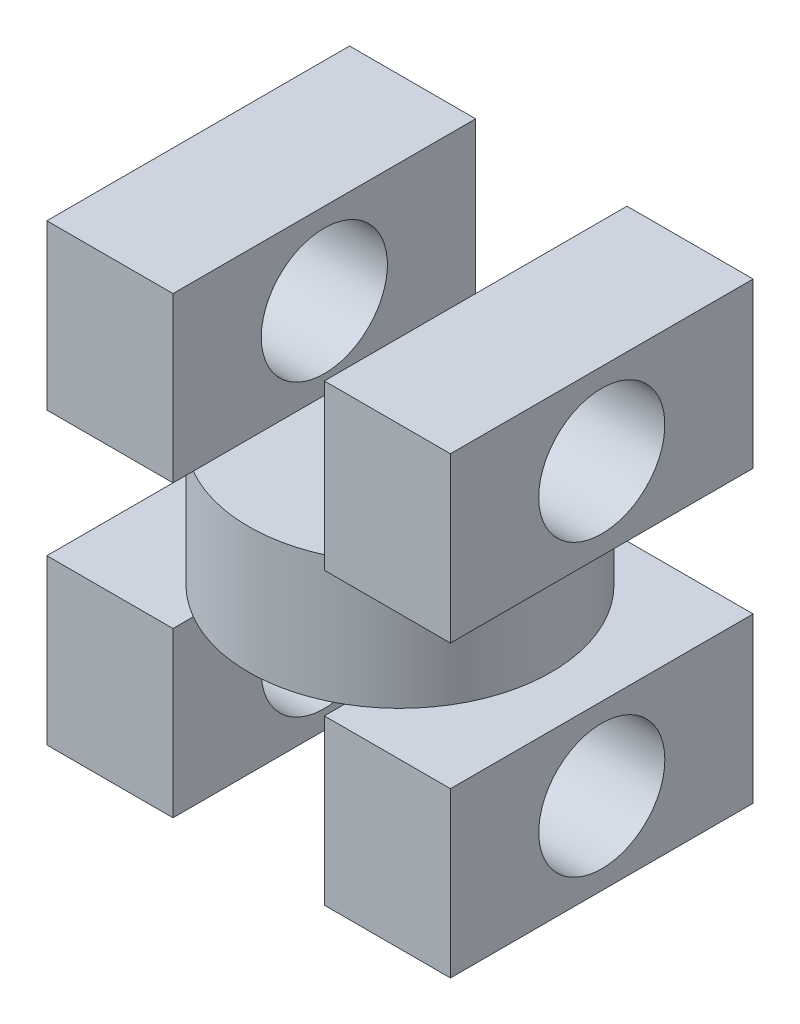
SolidWorks part; units mm, degrees
ref_plane "Front Plane" through (0, 0, 0) normal (0, 0, 1) x (1, 0, 0)
ref_plane "Top Plane" through (0, 0, 0) normal (0, 1, 0) x (1, 0, 0)
ref_plane "Right Plane" through (0, 0, 0) normal (1, 0, 0) x (0, 0, -1)
sketch "Sketch1" plane through (0, 0, 0) normal (0, 0, 1) x (1, 0, 0)
  line L0 (0, 0) -> (0, 13)
  line L1 (0, 13) -> (-32, 13)
  line L2 (-32, 13) -> (-32, 0)
  line L3 (-32, 0) -> (0, 0)
extrude "Boss-Extrude1" add sketch "Sketch1" along normal blind 24
sketch "Sketch2" plane through (0, 0, 0) normal (0, 0, -1) x (-1, 0, 0)
  line L0 (0, 13) -> (10, 13)
  line L1 (0, 13) -> (32, 13) construction
  line L2 (10, 13) -> (10, 0)
  line L3 (32, 0) -> (0, 0) construction
  line L4 (10, 0) -> (22, 0)
  line L5 (22, 0) -> (22, 13)
  line L6 (22, 13) -> (10, 13)
  line M1 (0, 0) -> (32, 0)
  line M3 (32, 13) -> (0, 13)
extrude "Cut-Extrude1" cut sketch "Sketch2" against normal through all contours L5 L2 M1 M3
sketch "Sketch3" plane through (0, 0, 0) normal (1, 0, 0) x (0, 0, -1)
  line L0 (0, 6.5) -> (-12, 6.5)
  line L1 (0, 0) -> (0, 13) construction
  circle A0 centre (-12, 6.5) radius 4.5
extrude "Cut-Extrude2" cut sketch "Sketch3" against normal through all
sketch "Sketch4" plane through (0, 0, 0) normal (0, -1, 0) x (-1, 0, 0)
  line L0 (22, -12) -> (10, -12)
  line L1 (22, -24) -> (22, 0) construction
  line L2 (10, -24) -> (10, 0) construction
  circle A0 centre (16, -12) radius 12
extrude "Boss-Extrude2" add sketch "Sketch4" along normal blind 10
ref_plane "Plane1" through (0, -5, 0) normal (0, 1, 0) x (1, 0, 0)
mirror "Mirror1" about plane through (0, -5, 0) normal (0, 1, 0) of "Cut-Extrude2", "Cut-Extrude1", "Boss-Extrude1"
sketch "Sketch5" plane through (0, 0, 0) normal (1, 0, 0) x (0, 0, -1)
  circle A0 centre (-12, -16.5) radius 5
extrude "Cut-Extrude3" cut sketch "Sketch5" against normal through all
sketch "Sketch6" plane through (-32, 0, 0) normal (-1, 0, 0) x (0, 0, 1)
  circle A0 centre (12, 6.5) radius 5
extrude "Cut-Extrude4" cut sketch "Sketch6" against normal through all
